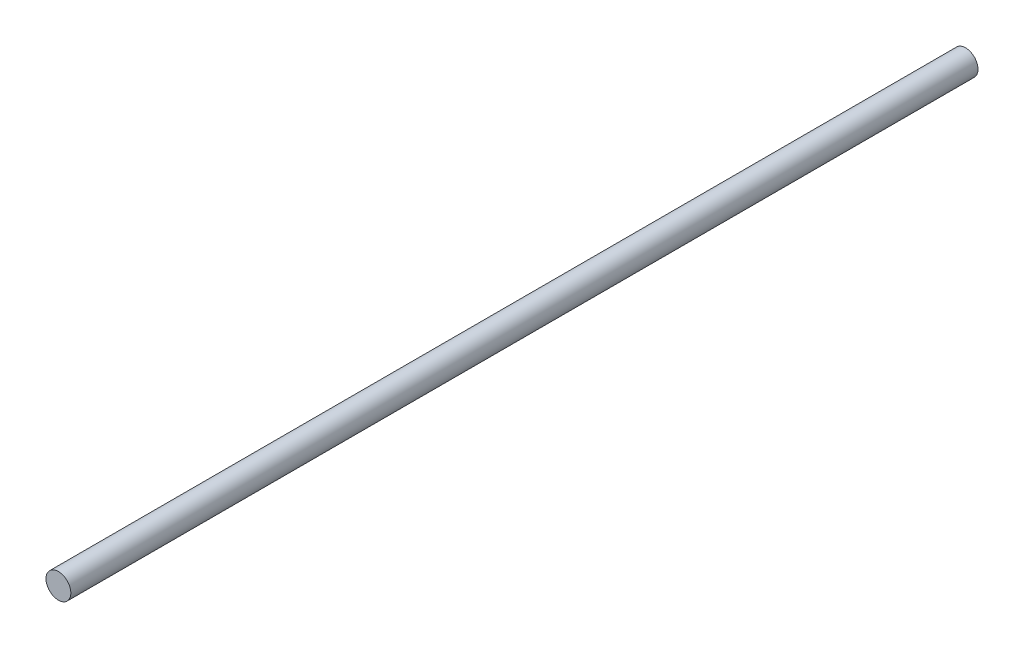
SolidWorks part; units mm, degrees
ref_plane "Front Plane" through (0, 0, 0) normal (0, 0, 1) x (1, 0, 0)
ref_plane "Top Plane" through (0, 0, 0) normal (0, 1, 0) x (1, 0, 0)
ref_plane "Right Plane" through (0, 0, 0) normal (1, 0, 0) x (0, 0, -1)
sketch "Sketch1" plane through (0, 0, 0) normal (0, 0, 1) x (1, 0, 0)
  circle A0 centre (0, 0) radius 6.35
  dimension "D1" = 12.7
extrude "Boss-Extrude1" add sketch "Sketch1" along normal blind 463.55
